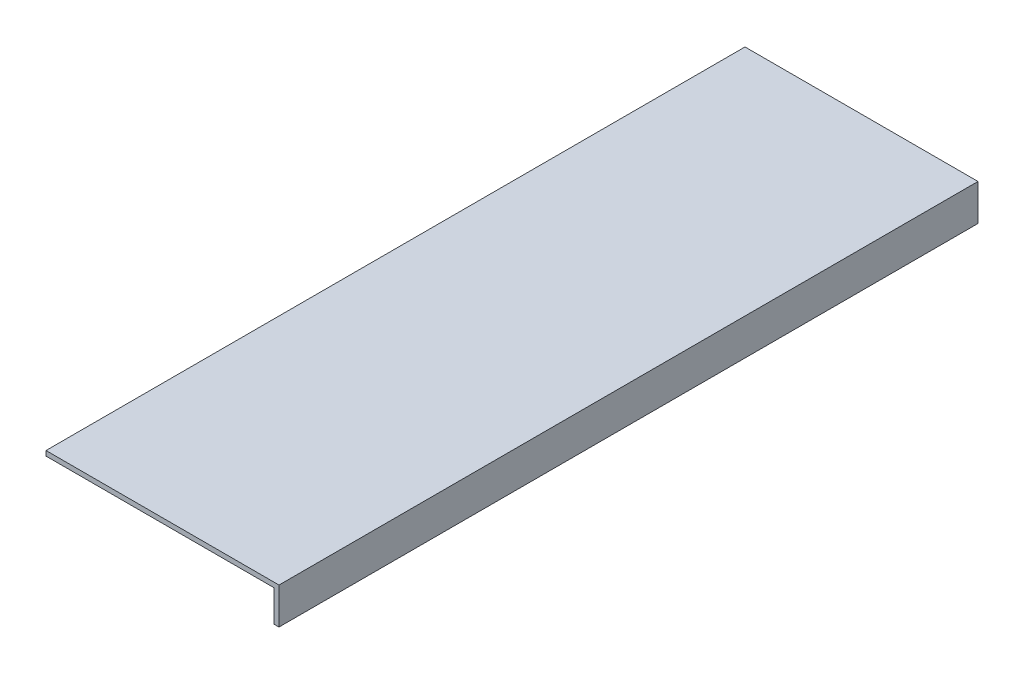
SolidWorks part; units mm, degrees
ref_plane "Front Plane" through (0, 0, 0) normal (0, 0, 1) x (1, 0, 0)
ref_plane "Top Plane" through (0, 0, 0) normal (0, 1, 0) x (1, 0, 0)
ref_plane "Right Plane" through (0, 0, 0) normal (1, 0, 0) x (0, 0, -1)
sketch "Sketch1" plane through (0, 0, 0) normal (0, 1, 0) x (1, 0, 0)
  line L1 (0, 0) -> (152.4, 0)
  line L2 (0, 0) -> (0, 457.2)
  line L3 (0, 457.2) -> (152.4, 457.2)
  line L4 (152.4, 0) -> (152.4, 457.2)
  dimension "D1" = 152.4
  dimension "D2" = 457.2
extrude "Boss-Extrude1" add sketch "Sketch1" along normal blind 3.175
sketch "Sketch2" plane through (0, 3.175, 0) normal (0, 1, 0) x (1, 0, 0)
  line L0 (0, 0) -> (152.4, 0) construction
  line L1 (152.4, 457.2) -> (149.225, 457.2)
  line L2 (152.4, 457.2) -> (152.4, 0)
  line L3 (152.4, 0) -> (149.225, 0)
  line L4 (149.225, 457.2) -> (149.225, 0)
  dimension "D1" = 3.175
extrude "Boss-Extrude2" add sketch "Sketch2" against normal blind 23.8125
sketch "Sketch3" plane through (0, 0, 0) normal (0, -1, 0) x (1, 0, 0)
  line L0 (0, -457.2) -> (0, 0) construction
  line L1 (0, -106.3625) -> (149.225, -106.3625)
  line L2 (0, -106.3625) -> (0, -109.5375)
  line L3 (0, -109.5375) -> (149.225, -109.5375)
  line L4 (149.225, -106.3625) -> (149.225, -109.5375)
  line L5 (149.225, 0) -> (149.225, -457.2) construction
  line L7 (149.225, -227.0125) -> (0, -227.0125)
  line L8 (149.225, -227.0125) -> (149.225, -230.1875)
  line L9 (149.225, -230.1875) -> (0, -230.1875)
  line L10 (0, -227.0125) -> (0, -230.1875)
  line L11 (149.225, -347.6625) -> (0, -347.6625)
  line L12 (149.225, -347.6625) -> (149.225, -350.8375)
  line L13 (149.225, -350.8375) -> (0, -350.8375)
  line L14 (0, -347.6625) -> (0, -350.8375)
  line L16 (0, 0) -> (149.225, 0) construction
  line L17 (0, 0) -> (149.225, 0)
  line L18 (0, 0) -> (0, -3.175)
  line L19 (0, -3.175) -> (149.225, -3.175)
  line L20 (149.225, 0) -> (149.225, -3.175)
  line L21 (149.225, -454.025) -> (0, -454.025)
  line L22 (149.225, -454.025) -> (149.225, -457.2)
  line L23 (149.225, -457.2) -> (0, -457.2)
  line L24 (0, -454.025) -> (0, -457.2)
  line L25 (149.225, -457.2) -> (0, -457.2) construction
  dimension "D1" = 3.175
  dimension "D2" = 3.175
  dimension "D3" = 3.175
  dimension "D4" = 3.175
  dimension "D5" = 117.475
  dimension "D6" = 117.475
  dimension "D7" = 3.175
  dimension "D8" = 103.1875
